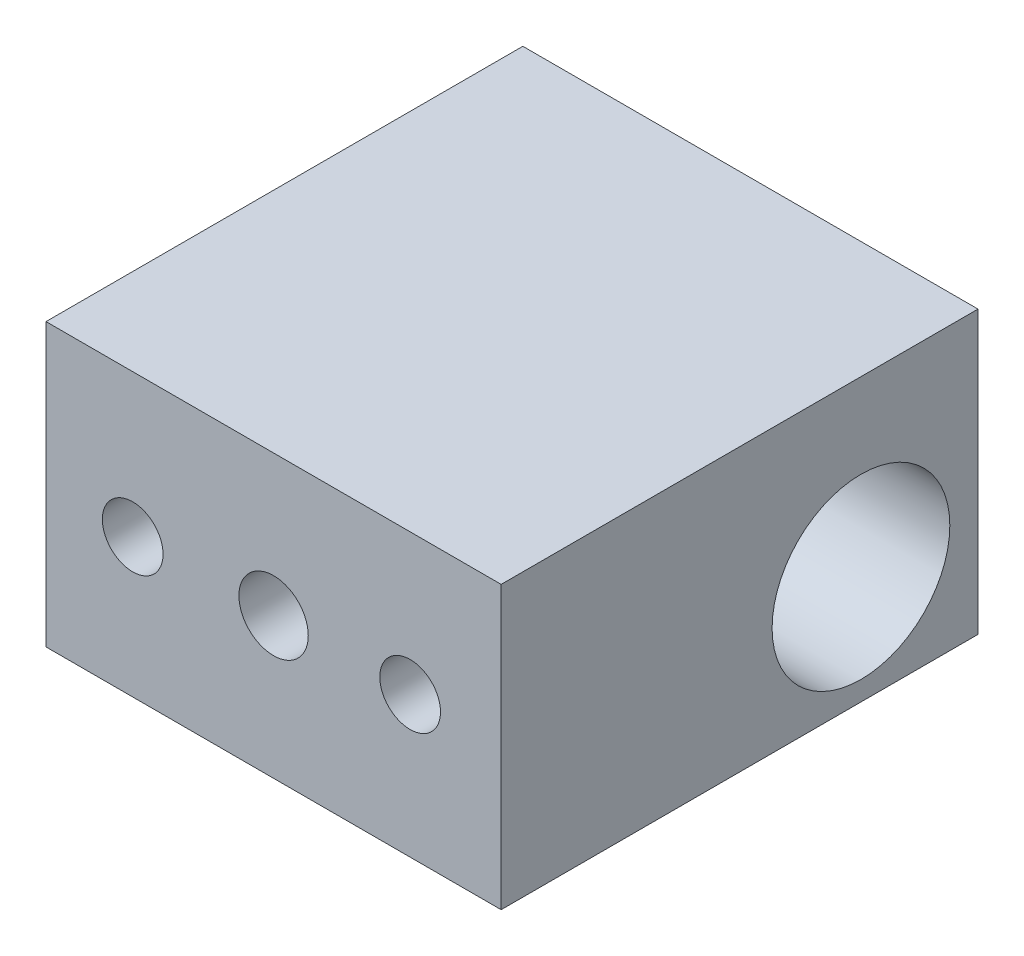
SolidWorks part; units mm, degrees
ref_plane "前视基准面" through (0, 0, 0) normal (0, 0, 1) x (1, 0, 0)
ref_plane "上视基准面" through (0, 0, 0) normal (0, 1, 0) x (1, 0, 0)
ref_plane "右视基准面" through (0, 0, 0) normal (1, 0, 0) x (0, 0, -1)
sketch "草图2" plane through (0, 0, 0) normal (0, 0, 1) x (1, 0, 0)
  line L1 (-52.5, 32.5) -> (52.5, 32.5)
  line L2 (-52.5, 32.5) -> (-52.5, -32.5)
  line L3 (-52.5, -32.5) -> (52.5, -32.5)
  line L4 (52.5, 32.5) -> (52.5, -32.5)
  line L5 (-52.5, 32.5) -> (52.5, -32.5) construction
  line L6 (-52.5, -32.5) -> (52.5, 32.5) construction
  point P0 (0, 0)
  dimension "D1" = 105
  dimension "D2" = 65
extrude "凸台-拉伸1" add sketch "草图2" against normal blind 110
sketch "草图3" plane through (0, 0, 0) normal (0, 0, 1) x (1, 0, 0)
  line L0 (-52.5, -32.5) -> (52.5, -32.5) construction
  line L1 (-52.5, 32.5) -> (-52.5, -32.5) construction
  circle A0 centre (-32.5, -0.5) radius 7
  circle A1 centre (0, 0) radius 8
  circle A2 centre (31.5, 0) radius 7
  dimension "D1" = 14
  dimension "D2" = 16
  dimension "D3" = 14
  dimension "D4" = 32
  dimension "D6" = 64
  dimension "D5" = 20
extrude "切除-拉伸1" cut sketch "草图3" against normal blind 50 contours A0 | A2 | A1
sketch "草图4" plane through (52.5, 0, 0) normal (1, 0, 0) x (0, 0, -1)
  line L0 (110, 32.5) -> (0, 32.5) construction
  line L1 (0, -32.5) -> (0, 32.5) construction
  circle A0 centre (83, -7.5) radius 20.5
  dimension "D1" = 41
  dimension "D2" = 40
  dimension "D3" = 83
extrude "切除-拉伸2" cut sketch "草图4" against normal through all
